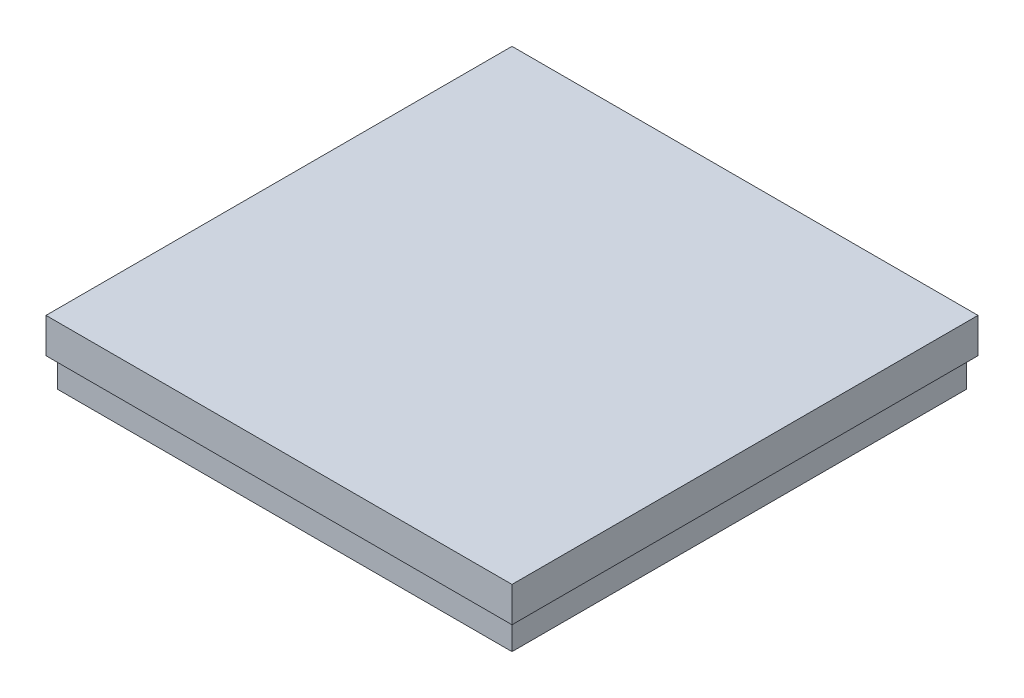
SolidWorks part; units mm, degrees
ref_plane "Front" through (0, 0, 0) normal (0, 0, 1) x (1, 0, 0)
ref_plane "Top" through (0, 0, 0) normal (0, 1, 0) x (1, 0, 0)
ref_plane "Right" through (0, 0, 0) normal (1, 0, 0) x (0, 0, -1)
sketch "Эскиз1" plane through (0, 0, 0) normal (0, 1, 0) x (1, 0, 0)
  line L1 (-16.7791, 6.6512) -> (22.2209, 6.6512)
  line L2 (-16.7791, 6.6512) -> (-16.7791, -32.3488)
  line L3 (-16.7791, -32.3488) -> (22.2209, -32.3488)
  line L4 (22.2209, 6.6512) -> (22.2209, -32.3488)
  dimension "D1" = 39
  dimension "D2" = 39
extrude "Бобышка-Вытянуть1" add sketch "Эскиз1" along normal blind 5.5
sketch "Эскиз2" plane through (-16.7791, 0, 0) normal (-1, 0, 0) x (0, 0, 1)
  line L0 (32.3488, 5.5) -> (32.3488, 0) construction
  line L1 (-6.6512, 5.5) -> (32.3488, 5.5)
  line L2 (-6.6512, 5.5) -> (-6.6512, 2.5)
  line L3 (-6.6512, 2.5) -> (32.3488, 2.5)
  line L4 (32.3488, 5.5) -> (32.3488, 2.5)
  dimension "D1" = 3
extrude "Бобышка-Вытянуть2" add sketch "Эскиз2" along normal blind 0.5
sketch "Эскиз3" plane through (0, 0, 32.3488) normal (0, 0, 1) x (1, 0, 0)
  line L0 (-17.2791, 5.5) -> (22.2209, 5.5) construction
  line L1 (-17.2791, 5.5) -> (22.2209, 5.5)
  line L2 (-17.2791, 5.5) -> (-17.2791, 2.5)
  line L3 (-17.2791, 2.5) -> (22.2209, 2.5)
  line L4 (22.2209, 5.5) -> (22.2209, 2.5)
  line L5 (-17.2791, 2.5) -> (-17.2791, 5.5) construction
  line L6 (22.2209, 5.5) -> (22.2209, 0) construction
  dimension "D1" = 3
extrude "Бобышка-Вытянуть3" add sketch "Эскиз3" along normal blind 0.5
sketch "Эскиз5" plane through (22.2209, 0, 0) normal (1, 0, 0) x (0, 0, -1)
  line L1 (-32.8488, 5.5) -> (6.6512, 5.5)
  line L2 (-32.8488, 5.5) -> (-32.8488, 2.5)
  line L3 (-32.8488, 2.5) -> (6.6512, 2.5)
  line L4 (6.6512, 5.5) -> (6.6512, 2.5)
extrude "Бобышка-Вытянуть4" add sketch "Эскиз5" along normal blind 0.5
sketch "Эскиз6" plane through (0, 0, -6.6512) normal (0, 0, -1) x (-1, 0, 0)
  line L1 (-22.7209, 5.5) -> (17.2791, 5.5)
  line L2 (-22.7209, 5.5) -> (-22.7209, 2.5)
  line L3 (-22.7209, 2.5) -> (17.2791, 2.5)
  line L4 (17.2791, 5.5) -> (17.2791, 2.5)
extrude "Бобышка-Вытянуть5" add sketch "Эскиз6" along normal blind 0.5
sketch "Эскиз7" plane through (0, 0, 0) normal (0, -1, 0) x (1, 0, 0)
  line L0 (-16.7791, 32.3488) -> (22.2209, 32.3488) construction
  line L1 (-16.2791, 31.8488) -> (21.7209, 31.8488)
  line L2 (-16.2791, 31.8488) -> (-16.2791, -6.1512)
  line L3 (-16.2791, -6.1512) -> (21.7209, -6.1512)
  line L4 (21.7209, 31.8488) -> (21.7209, -6.1512)
  line L5 (22.2209, -6.6512) -> (-16.7791, -6.6512) construction
  line L6 (-16.7791, -6.6512) -> (-16.7791, 32.3488) construction
  line L7 (22.2209, 32.3488) -> (22.2209, -6.6512) construction
  dimension "D1" = 0.5
  dimension "D2" = 0.5
  dimension "D3" = 0.5
  dimension "D4" = 0.5
extrude "Вырез-Вытянуть1" cut sketch "Эскиз7" against normal blind 4.5
sketch "Эскиз8" plane through (0, 5.5, 0) normal (0, 1, 0) x (1, 0, 0)
  text T0 "%" font "Century Gothic" height in points 36
  text T1 "ºC" font "Century Gothic" height in points 36
